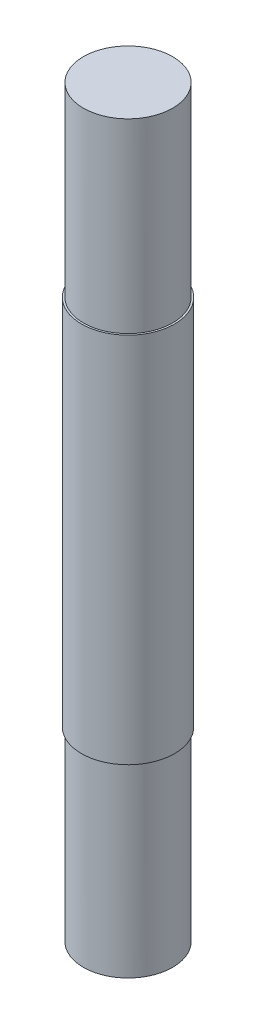
SolidWorks part; units mm, degrees
ref_plane "前视基准面" through (0, 0, 0) normal (0, 0, 1) x (1, 0, 0)
ref_plane "上视基准面" through (0, 0, 0) normal (0, 1, 0) x (1, 0, 0)
ref_plane "右视基准面" through (0, 0, 0) normal (1, 0, 0) x (0, 0, -1)
other "Configuration Table"
sketch "草图1" plane through (0, 0, 0) normal (0, 1, 0) x (1, 0, 0)
  circle A0 centre (0, 0) radius 2.4
  dimension "D1" = 4.8
extrude "凸台-拉伸1" add sketch "草图1" along normal blind 40
ref_plane "基准面1" through (0, 20, 0) normal (0, -1, 0) x (-1, 0, 0)
sketch "草图2" plane through (0, 20, 0) normal (0, -1, 0) x (-1, 0, 0)
  circle A0 centre (0, 0) radius 2.5
  dimension "D1" = 5
extrude "凸台-拉伸2" add sketch "草图2" along normal mid plane 20
